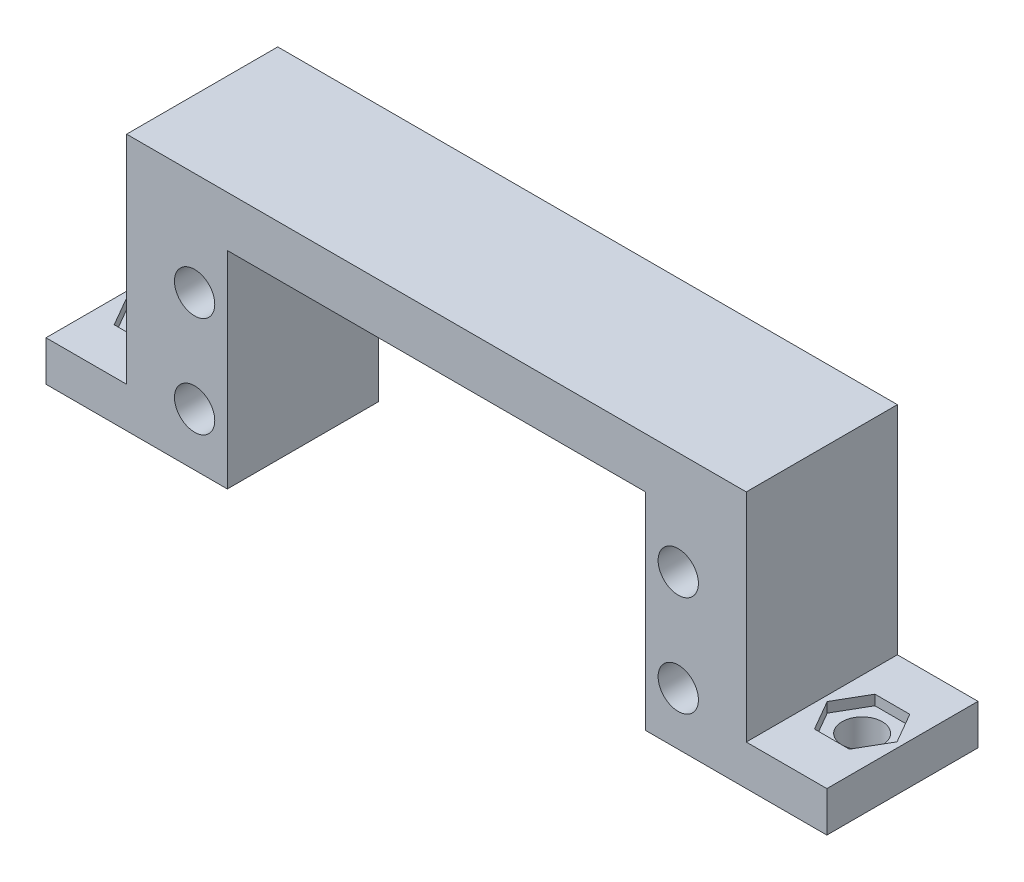
SolidWorks part; units mm, degrees
ref_plane "Front Plane" through (0, 0, 0) normal (0, 0, 1) x (1, 0, 0)
ref_plane "Top Plane" through (0, 0, 0) normal (0, 1, 0) x (1, 0, 0)
ref_plane "Right Plane" through (0, 0, 0) normal (1, 0, 0) x (0, 0, -1)
sketch "Sketch1" plane through (0, 0, 0) normal (0, 0, 1) x (1, 0, 0)
  line L0 (0, 0) -> (0, 20.5)
  line L1 (0, 20.5) -> (41.5, 20.5)
  line L2 (41.5, 20.5) -> (41.5, 0)
  line L3 (41.5, 0) -> (59.5, 0)
  line L4 (59.5, 0) -> (59.5, 4)
  line L5 (59.5, 4) -> (51.5, 4)
  line L6 (51.5, 4) -> (51.5, 25.5)
  line L7 (51.5, 25.5) -> (-10, 25.5)
  line L8 (-10, 25.5) -> (-10, 4)
  line L9 (-10, 4) -> (-18, 4)
  line L10 (-18, 4) -> (-18, 0)
  line L11 (-18, 0) -> (0, 0)
  line L12 (44.75, 15.25) -> (44.75, 5.25) construction
  line L13 (-3.25, 5.25) -> (-3.25, 15.25) construction
  circle A0 centre (44.75, 5.25) radius 2
  circle A1 centre (44.75, 15.25) radius 2
  circle A2 centre (-3.25, 15.25) radius 2
  circle A3 centre (-3.25, 5.25) radius 2
  point P17 (41.5, 10.25)
  point P18 (44.75, 10.25)
  point P21 (-3.25, 10.25)
  point P22 (0, 10.25)
  point P25 (20.75, 20.5)
  dimension "D11" = 4
  dimension "D12" = 4
  dimension "D15" = 24
  dimension "D16" = 4
  dimension "D17" = 4
  dimension "D1" = 20.5
  dimension "D2" = 41.5
  dimension "D3" = 5
  dimension "D4" = 10
  dimension "D5" = 10
  dimension "D6" = 4
  dimension "D7" = 8
  dimension "D8" = 4
  dimension "D9" = 8
  dimension "D10" = 24
  dimension "D13" = 10
  dimension "D14" = 10
extrude "Boss-Extrude1" add sketch "Sketch1" along normal blind 15
sketch "Sketch3" plane through (0, 0, 0) normal (0, 0, -1) x (-1, 0, 0)
  line L37 (3.25, 18.7141) -> (0.25, 16.9821)
  line L38 (0.25, 16.9821) -> (0.25, 13.5179)
  line L39 (0.25, 13.5179) -> (3.25, 11.7859)
  line L40 (3.25, 11.7859) -> (6.25, 13.5179)
  line L41 (6.25, 13.5179) -> (6.25, 16.9821)
  line L42 (6.25, 16.9821) -> (3.25, 18.7141)
  line L43 (3.25, 8.7141) -> (0.25, 6.9821)
  line L44 (0.25, 6.9821) -> (0.25, 3.5179)
  line L45 (0.25, 3.5179) -> (3.25, 1.7859)
  line L46 (3.25, 1.7859) -> (6.25, 3.5179)
  line L47 (6.25, 3.5179) -> (6.25, 6.9821)
  line L48 (6.25, 6.9821) -> (3.25, 8.7141)
  line L49 (-44.75, 18.7141) -> (-47.75, 16.9821)
  line L50 (-47.75, 16.9821) -> (-47.75, 13.5179)
  line L51 (-47.75, 13.5179) -> (-44.75, 11.7859)
  line L52 (-44.75, 11.7859) -> (-41.75, 13.5179)
  line L53 (-41.75, 13.5179) -> (-41.75, 16.9821)
  line L54 (-41.75, 16.9821) -> (-44.75, 18.7141)
  line L55 (-45.0377, 8.7021) -> (-47.8835, 6.7269)
  line L56 (-47.8835, 6.7269) -> (-47.5958, 3.2748)
  line L57 (-47.5958, 3.2748) -> (-44.4623, 1.7979)
  line L58 (-44.4623, 1.7979) -> (-41.6165, 3.7731)
  line L59 (-41.6165, 3.7731) -> (-41.9042, 7.2252)
  line L60 (-41.9042, 7.2252) -> (-45.0377, 8.7021)
  circle A0 centre (-44.75, 15.25) radius 3 construction
  circle A1 centre (-44.75, 5.25) radius 3 construction
  circle A2 centre (3.25, 15.25) radius 3 construction
  circle A3 centre (3.25, 5.25) radius 3 construction
  point P11 (-41.7604, 5.4991)
  dimension "D1" = 6
  dimension "D2" = 6
  dimension "D3" = 6
  dimension "D4" = 6
extrude "Cut-Extrude1" cut sketch "Sketch3" against normal offset from surface (11 mm away) 4 up to face at (-1.25, 15.25, 15)
sketch "Sketch4" plane through (0, 4, 0) normal (0, 1, 0) x (1, 0, 0)
  line L0 (59.5, -15) -> (51.5, 0) construction
  line L1 (-10, -15) -> (-18, 0) construction
  line L3 (58.9641, -7.5) -> (57.2321, -4.5)
  line L4 (57.2321, -4.5) -> (53.7679, -4.5)
  line L5 (53.7679, -4.5) -> (52.0359, -7.5)
  line L6 (52.0359, -7.5) -> (53.7679, -10.5)
  line L7 (53.7679, -10.5) -> (57.2321, -10.5)
  line L8 (57.2321, -10.5) -> (58.9641, -7.5)
  line L9 (-17.4641, -7.5) -> (-15.7321, -10.5)
  line L10 (-15.7321, -10.5) -> (-12.2679, -10.5)
  line L11 (-12.2679, -10.5) -> (-10.5359, -7.5)
  line L12 (-10.5359, -7.5) -> (-12.2679, -4.5)
  line L13 (-12.2679, -4.5) -> (-15.7321, -4.5)
  line L14 (-15.7321, -4.5) -> (-17.4641, -7.5)
  circle A0 centre (55.5, -7.5) radius 3 construction
  circle A1 centre (-14, -7.5) radius 3 construction
  dimension "D1" = 6
  dimension "D2" = 6
extrude "Cut-Extrude2" cut sketch "Sketch4" against normal blind 1 contours L3 L4 L5 L6 L7 L8 | L9 L10 L11 L12 L13 L14
sketch "Sketch5" plane through (0, 4, 0) normal (0, 1, 0) x (1, 0, 0)
  line L0 (59.5, -15) -> (51.5, 0) construction
  line L1 (-10, -15) -> (-18, 0) construction
  circle A0 centre (55.5, -7.5) radius 2
  circle A1 centre (-14, -7.5) radius 2
  dimension "D1" = 4
  dimension "D2" = 4
extrude "Cut-Extrude3" cut sketch "Sketch5" against normal up to surface (4 mm away) up to face at (50.5, 0, 7.5)
sketch "Sketch6" plane through (0, 0, 0) normal (0, -1, 0) x (1, 0, 0)
  circle A0 centre (-14, 7.5) radius 2
  circle A1 centre (55.5, 7.5) radius 2
  dimension "D1" = 69.5
